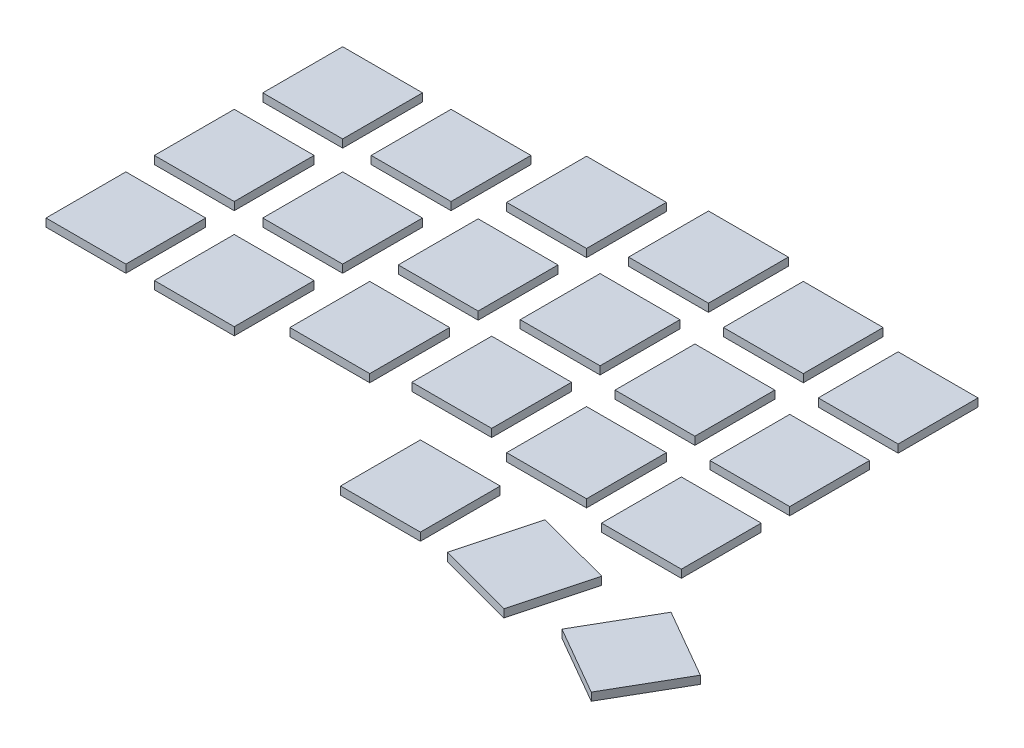
SolidWorks part; units mm, degrees
ref_plane "Front Plane" through (0, 0, 0) normal (0, 0, 1) x (1, 0, 0)
ref_plane "Top Plane" through (0, 0, 0) normal (0, 1, 0) x (1, 0, 0)
ref_plane "Right Plane" through (0, 0, 0) normal (1, 0, 0) x (0, 0, -1)
sketch "Sketch1" plane through (0, 0, 0) normal (0, 1, 0) x (1, 0, 0)
  line L0 (-49.2053, 38.6298) -> (-35.2053, 38.6298)
  line L1 (-49.2053, 38.6298) -> (-49.2053, 24.6298)
  line L2 (-49.2053, 24.6298) -> (-35.2053, 24.6298)
  line L3 (-35.2053, 38.6298) -> (-35.2053, 24.6298)
  line L4 (-49.2053, 38.6298) -> (-35.2053, 24.6298) construction
  line L5 (-49.2053, 24.6298) -> (-35.2053, 38.6298) construction
  line L6 (-49.2053, 19.6285) -> (-35.2053, 19.6285)
  line L7 (-49.2053, 19.6285) -> (-49.2053, 5.6285)
  line L8 (-49.2053, 5.6285) -> (-35.2053, 5.6285)
  line L9 (-35.2053, 19.6285) -> (-35.2053, 5.6285)
  line L10 (-49.2053, 19.6285) -> (-35.2053, 5.6285) construction
  line L11 (-49.2053, 5.6285) -> (-35.2053, 19.6285) construction
  line L12 (-49.2053, 0.6271) -> (-35.2053, 0.6271)
  line L13 (-49.2053, 0.6271) -> (-49.2053, -13.3729)
  line L14 (-49.2053, -13.3729) -> (-35.2053, -13.3729)
  line L15 (-35.2053, 0.6271) -> (-35.2053, -13.3729)
  line L16 (-49.2053, 0.6271) -> (-35.2053, -13.3729) construction
  line L17 (-49.2053, -13.3729) -> (-35.2053, 0.6271) construction
  line L18 (-30.2034, 38.6298) -> (-16.2034, 38.6298)
  line L19 (-30.2034, 38.6298) -> (-30.2034, 24.6298)
  line L20 (-30.2034, 24.6298) -> (-16.2034, 24.6298)
  line L21 (-16.2034, 38.6298) -> (-16.2034, 24.6298)
  line L22 (-30.2034, 38.6298) -> (-16.2034, 24.6298) construction
  line L23 (-30.2034, 24.6298) -> (-16.2034, 38.6298) construction
  line L24 (-30.2034, 19.6285) -> (-16.2034, 19.6285)
  line L25 (-30.2034, 19.6285) -> (-30.2034, 5.6285)
  line L26 (-30.2034, 5.6285) -> (-16.2034, 5.6285)
  line L27 (-16.2034, 19.6285) -> (-16.2034, 5.6285)
  line L28 (-30.2034, 19.6285) -> (-16.2034, 5.6285) construction
  line L29 (-30.2034, 5.6285) -> (-16.2034, 19.6285) construction
  line L30 (-30.2034, 0.6271) -> (-16.2034, 0.6271)
  line L31 (-30.2034, 0.6271) -> (-30.2034, -13.3729)
  line L32 (-30.2034, -13.3729) -> (-16.2034, -13.3729)
  line L33 (-16.2034, 0.6271) -> (-16.2034, -13.3729)
  line L34 (-30.2034, 0.6271) -> (-16.2034, -13.3729) construction
  line L35 (-30.2034, -13.3729) -> (-16.2034, 0.6271) construction
  line L36 (-11.2021, 43.3802) -> (2.7979, 43.3802)
  line L37 (-11.2021, 43.3802) -> (-11.2021, 29.3802)
  line L38 (-11.2021, 29.3802) -> (2.7979, 29.3802)
  line L39 (2.7979, 43.3802) -> (2.7979, 29.3802)
  line L40 (-11.2021, 43.3802) -> (2.7979, 29.3802) construction
  line L41 (-11.2021, 29.3802) -> (2.7979, 43.3802) construction
  line L42 (-11.2021, 24.3788) -> (2.7979, 24.3788)
  line L43 (-11.2021, 24.3788) -> (-11.2021, 10.3788)
  line L44 (-11.2021, 10.3788) -> (2.7979, 10.3788)
  line L45 (2.7979, 24.3788) -> (2.7979, 10.3788)
  line L46 (-11.2021, 24.3788) -> (2.7979, 10.3788) construction
  line L47 (-11.2021, 10.3788) -> (2.7979, 24.3788) construction
  line L48 (-11.2021, 5.3775) -> (2.7979, 5.3775)
  line L49 (-11.2021, 5.3775) -> (-11.2021, -8.6225)
  line L50 (-11.2021, -8.6225) -> (2.7979, -8.6225)
  line L51 (2.7979, 5.3775) -> (2.7979, -8.6225)
  line L52 (-11.2021, 5.3775) -> (2.7979, -8.6225) construction
  line L53 (-11.2021, -8.6225) -> (2.7979, 5.3775) construction
  line L54 (7.7993, 45.7553) -> (21.7993, 45.7553)
  line L55 (7.7993, 45.7553) -> (7.7993, 31.7553)
  line L56 (7.7993, 31.7553) -> (21.7993, 31.7553)
  line L57 (21.7993, 45.7553) -> (21.7993, 31.7553)
  line L58 (7.7993, 45.7553) -> (21.7993, 31.7553) construction
  line L59 (7.7993, 31.7553) -> (21.7993, 45.7553) construction
  line L60 (7.7993, 26.754) -> (21.7993, 26.754)
  line L61 (7.7993, 26.754) -> (7.7993, 12.754)
  line L62 (7.7993, 12.754) -> (21.7993, 12.754)
  line L63 (21.7993, 26.754) -> (21.7993, 12.754)
  line L64 (7.7993, 26.754) -> (21.7993, 12.754) construction
  line L65 (7.7993, 7.7526) -> (21.7993, 7.7526)
  line L66 (7.7993, 7.7526) -> (7.7993, -6.2474)
  line L67 (7.7993, -6.2474) -> (21.7993, -6.2474)
  line L68 (21.7993, 7.7526) -> (21.7993, -6.2474)
  line L69 (7.7993, 7.7526) -> (21.7993, -6.2474) construction
  line L70 (7.7993, -6.2474) -> (21.7993, 7.7526) construction
  line L71 (7.7993, 12.754) -> (21.7993, 26.754) construction
  line L72 (26.8006, 43.3802) -> (40.8006, 43.3802)
  line L73 (26.8006, 43.3802) -> (26.8006, 29.3802)
  line L74 (26.8006, 29.3802) -> (40.8006, 29.3802)
  line L75 (40.8006, 43.3802) -> (40.8006, 29.3802)
  line L76 (26.8006, 43.3802) -> (40.8006, 29.3802) construction
  line L77 (26.8006, 29.3802) -> (40.8006, 43.3802) construction
  line L78 (26.8006, 24.3788) -> (40.8006, 24.3788)
  line L79 (26.8006, 24.3788) -> (26.8006, 10.3788)
  line L80 (26.8006, 10.3788) -> (40.8006, 10.3788)
  line L81 (40.8006, 24.3788) -> (40.8006, 10.3788)
  line L82 (26.8006, 24.3788) -> (40.8006, 10.3788) construction
  line L83 (26.8006, 10.3788) -> (40.8006, 24.3788) construction
  line L84 (26.8006, 5.3775) -> (40.8006, 5.3775)
  line L85 (26.8006, 5.3775) -> (26.8006, -8.6225)
  line L86 (26.8006, -8.6225) -> (40.8006, -8.6225)
  line L87 (40.8006, 5.3775) -> (40.8006, -8.6225)
  line L88 (26.8006, 5.3775) -> (40.8006, -8.6225) construction
  line L89 (26.8006, -8.6225) -> (40.8006, 5.3775) construction
  line L90 (45.802, 41.005) -> (59.802, 41.005)
  line L91 (45.802, 41.005) -> (45.802, 27.005)
  line L92 (45.802, 27.005) -> (59.802, 27.005)
  line L93 (59.802, 41.005) -> (59.802, 27.005)
  line L94 (45.802, 41.005) -> (59.802, 27.005) construction
  line L95 (45.802, 27.005) -> (59.802, 41.005) construction
  line L96 (45.802, 22.0036) -> (59.802, 22.0036)
  line L97 (45.802, 22.0036) -> (45.802, 8.0036)
  line L98 (45.802, 8.0036) -> (59.802, 8.0036)
  line L99 (59.802, 22.0036) -> (59.802, 8.0036)
  line L100 (45.802, 22.0036) -> (59.802, 8.0036) construction
  line L101 (45.802, 8.0036) -> (59.802, 22.0036) construction
  line L102 (45.802, 3.0023) -> (59.802, 3.0023)
  line L103 (45.802, 3.0023) -> (45.802, -10.9977)
  line L104 (45.802, -10.9977) -> (59.802, -10.9977)
  line L105 (59.802, 3.0023) -> (59.802, -10.9977)
  line L106 (45.802, 3.0023) -> (59.802, -10.9977) construction
  line L107 (45.802, -10.9977) -> (59.802, 3.0023) construction
  line L108 (17.3, -14.2489) -> (31.3, -14.2489)
  line L109 (17.3, -14.2489) -> (17.3, -28.2489)
  line L110 (17.3, -28.2489) -> (31.3, -28.2489)
  line L111 (31.3, -14.2489) -> (31.3, -28.2489)
  line L112 (17.3, -14.2489) -> (31.3, -28.2489) construction
  line L113 (17.3, -28.2489) -> (31.3, -14.2489) construction
  line L114 (40.3508, -15.4318) -> (36.7411, -28.9584)
  line L115 (40.3508, -15.4318) -> (53.8775, -19.0415)
  line L116 (36.7411, -28.9584) -> (50.2677, -32.5681)
  line L117 (53.8775, -19.0415) -> (50.2677, -32.5681)
  line L118 (40.3508, -15.4318) -> (50.2677, -32.5681) construction
  line L119 (36.7411, -28.9584) -> (53.8775, -19.0415) construction
  line L120 (65.4305, -18.4374) -> (58.4388, -30.5666)
  line L121 (65.4305, -18.4374) -> (77.5596, -25.4291)
  line L122 (58.4388, -30.5666) -> (70.5679, -37.5583)
  line L123 (77.5596, -25.4291) -> (70.5679, -37.5583)
  line L124 (65.4305, -18.4374) -> (70.5679, -37.5583) construction
  line L125 (58.4388, -30.5666) -> (77.5596, -25.4291) construction
  point P0 (-42.2053, 31.6298)
  point P5 (-42.2053, 12.6285)
  point P10 (-42.2053, -6.3729)
  point P15 (-23.2034, 31.6298)
  point P20 (-23.2034, 12.6285)
  point P25 (-23.2034, -6.3729)
  point P30 (-4.2021, 36.3802)
  point P35 (-4.2021, 17.3788)
  point P40 (-4.2021, -1.6225)
  point P45 (14.7993, 38.7553)
  point P50 (14.7993, 19.754)
  point P55 (14.7993, 0.7526)
  point P60 (33.8006, 36.3802)
  point P65 (33.8006, 17.3788)
  point P70 (33.8006, -1.6225)
  point P75 (52.802, 34.005)
  point P80 (52.802, 15.0036)
  point P85 (52.802, -3.9977)
  point P90 (24.3, -21.2489)
  point P95 (45.3093, -24)
  point P96 (67.9992, -27.9979)
  dimension "D1" = 14
extrude "Boss-Extrude1" add sketch "Sketch1" along normal blind 1.397
